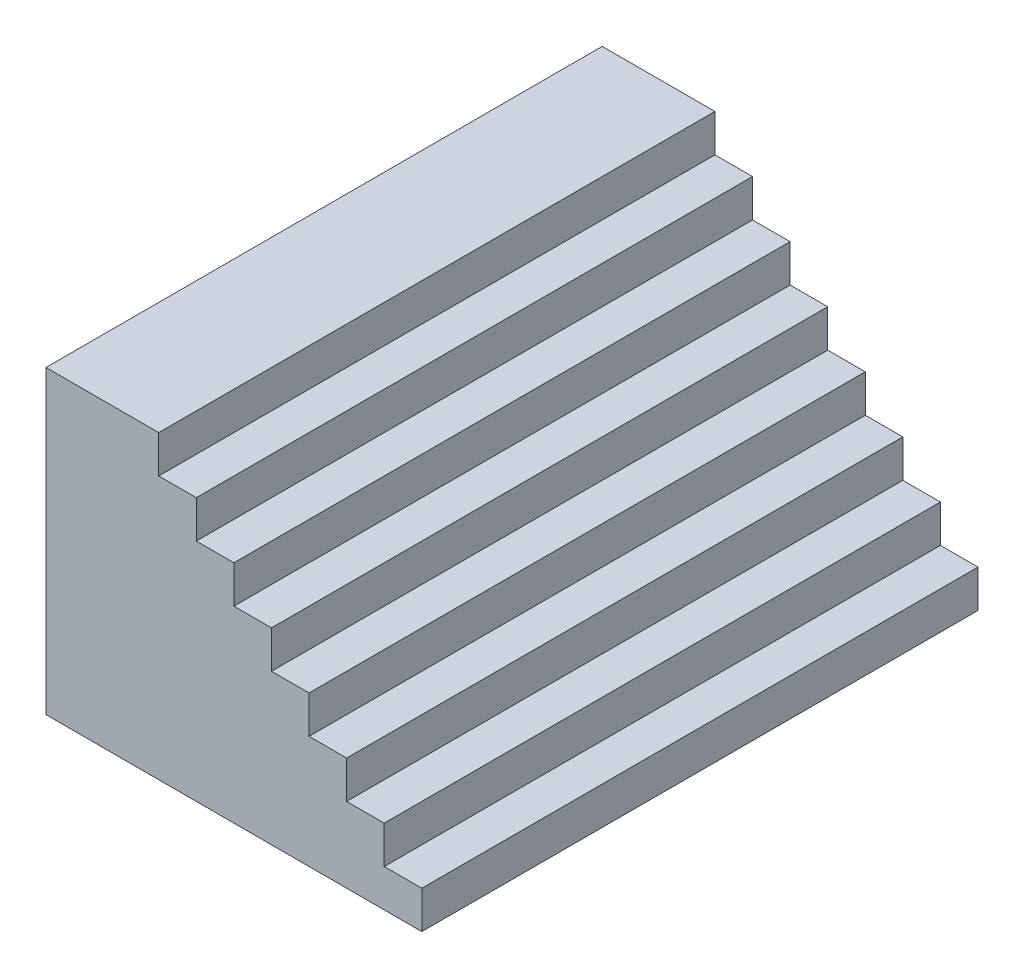
SolidWorks part; units mm, degrees
ref_plane "Front Plane" through (0, 0, 0) normal (0, 0, 1) x (1, 0, 0)
ref_plane "Top Plane" through (0, 0, 0) normal (0, 1, 0) x (1, 0, 0)
ref_plane "Right Plane" through (0, 0, 0) normal (1, 0, 0) x (0, 0, -1)
sketch "Sketch1" plane through (0, 0, 0) normal (1, 0, 0) x (0, 0, -1)
  line L1 (-1850, 1000) -> (1850, 1000)
  line L2 (-1850, 1000) -> (-1850, -1000)
  line L3 (-1850, -1000) -> (1850, -1000)
  line L4 (1850, 1000) -> (1850, -1000)
  line L5 (-1850, 1000) -> (1850, -1000) construction
  line L6 (-1850, -1000) -> (1850, 1000) construction
  point P0 (0, 0)
  dimension "D1" = 2000
  dimension "D2" = 3700
extrude "Boss-Extrude1" add sketch "Sketch1" along normal blind 2500 contours L1 L4 L3 L2
sketch "Sketch4" plane through (0, 0, 1850) normal (0, 0, 1) x (1, 0, 0)
  line L1 (2500, 1000) -> (2500, -1000) construction
  line L2 (2500, -750) -> (2250, -750)
  line L3 (2250, -750) -> (2250, -500)
  line L4 (2250, -500) -> (2000, -500)
  line L5 (2000, -500) -> (2000, -250)
  line L6 (2000, -250) -> (1750, -250)
  line L7 (1750, -250) -> (1750, 0)
  line L8 (1750, 0) -> (1500, 0)
  line L9 (1500, 0) -> (1500, 250)
  line L10 (1500, 250) -> (1250, 250)
  line L11 (1250, 250) -> (1250, 500)
  line L12 (1250, 500) -> (1000, 500)
  line L13 (1000, 500) -> (1000, 750)
  line L14 (1000, 750) -> (750, 750)
  line L15 (750, 750) -> (750, 1000)
  line L16 (2500, 1000) -> (0, 1000) construction
  line L17 (750, 1000) -> (2500, 1000)
  line L18 (2500, 1000) -> (2500, -750)
  dimension "D1" = 250
  dimension "D3" = 250
  dimension "D4" = 250
  dimension "D5" = 250
  dimension "D6" = 250
  dimension "D7" = 250
  dimension "D8" = 250
  dimension "D9" = 250
  dimension "D10" = 250
  dimension "D11" = 250
  dimension "D12" = 250
  dimension "D13" = 250
  dimension "D14" = 250
extrude "Cut-Extrude1" cut sketch "Sketch4" against normal blind 5000
